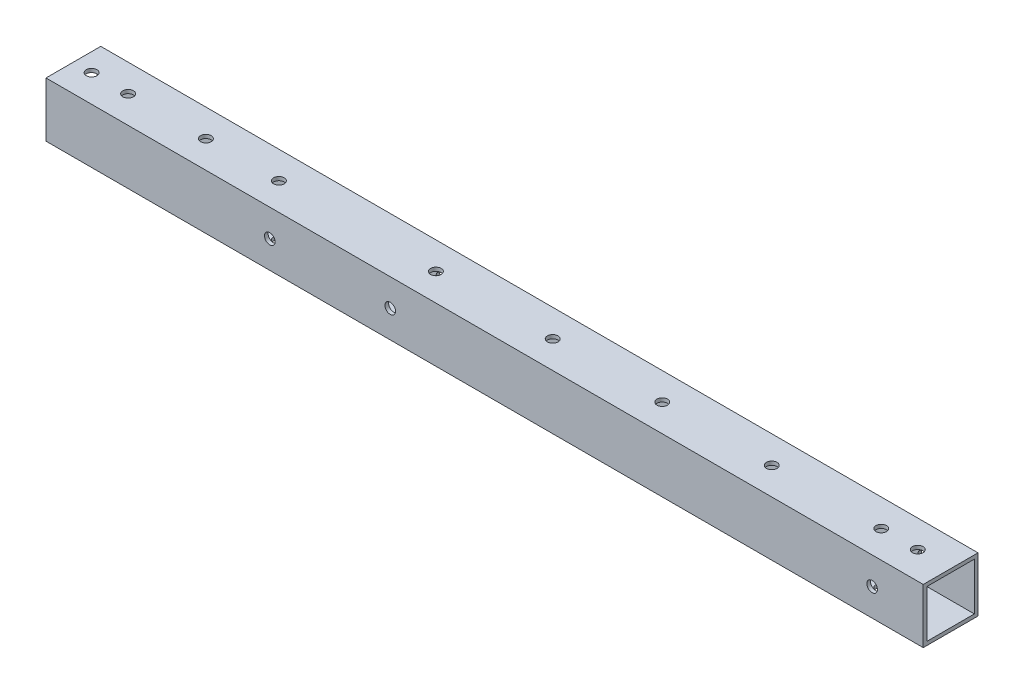
SolidWorks part; units mm, degrees
material "Thornel Mat VMA"
ref_plane "前视基准面" through (0, 0, 0) normal (0, 0, 1) x (1, 0, 0)
ref_plane "上视基准面" through (0, 0, 0) normal (0, 1, 0) x (1, 0, 0)
ref_plane "右视基准面" through (0, 0, 0) normal (1, 0, 0) x (0, 0, -1)
other "Configuration Table"
sketch "草图1" plane through (0, 0, 0) normal (1, 0, 0) x (0, 0, -1)
  line L0 (-6.5, -6.5) -> (-6.5, 6.5)
  line L1 (-7.5, -7.5) -> (7.5, -7.5)
  line L2 (-7.5, -7.5) -> (-7.5, 7.5)
  line L3 (-7.5, 7.5) -> (7.5, 7.5)
  line L4 (7.5, -7.5) -> (7.5, 7.5)
  line L5 (-7.5, -7.5) -> (7.5, 7.5) construction
  line L6 (-7.5, 7.5) -> (7.5, -7.5) construction
  line L7 (-6.5, 6.5) -> (6.5, 6.5)
  line L8 (6.5, -6.5) -> (6.5, 6.5)
  line L9 (-6.5, -6.5) -> (6.5, -6.5)
  point P0 (0, 0)
  dimension "D1" = 15
  dimension "D2" = 15
  dimension "D3" = 1
extrude "凸台-拉伸1" add sketch "草图1" along normal blind 240.3
sketch "草图2" plane through (0, 7.5, 0) normal (0, 1, 0) x (1, 0, 0)
  line L0 (0, 0) -> (271.1797, 0) construction
  circle A0 centre (5, 0) radius 1.45 construction
  circle A1 centre (15, 0) radius 1.45 construction
  circle A2 centre (36.3015, 0) radius 1.45 construction
  circle A3 centre (56.3015, 0) radius 1.45 construction
  circle A4 centre (99.3015, 0) radius 1.45 construction
  circle A5 centre (221.3015, 0) radius 1.45 construction
  circle A6 centre (231.3015, 0) radius 1.45 construction
  circle A7 centre (5, 0) radius 1.45
  circle A8 centre (15, 0) radius 1.45
  circle A9 centre (36.3015, 0) radius 1.45
  circle A10 centre (56.3015, 0) radius 1.45
  circle A11 centre (99.3015, 0) radius 1.45
  circle A12 centre (221.3015, 0) radius 1.45
  circle A13 centre (231.3015, 0) radius 1.45
  circle A14 centre (131.3015, 0) radius 1.45
  circle A15 centre (161.3015, 0) radius 1.45
  circle A16 centre (191.3015, 0) radius 1.45
  point P30 (161.3015, 0)
  dimension "D1" = 32
  dimension "D2" = 2.9
  dimension "D3" = 30
  dimension "D4" = 30
extrude "切除-拉伸1" cut sketch "草图2" against normal through all
sketch "草图3" plane through (0, 0, 7.5) normal (0, 0, 1) x (1, 0, 0)
  circle A0 centre (61.3015, 0) radius 1.45 construction
  circle A1 centre (61.3015, 0) radius 1.45
  circle A2 centre (226.3015, 0) radius 1.45 construction
  circle A3 centre (94.3015, 0) radius 1.45 construction
  circle A4 centre (226.3015, 0) radius 1.45
  circle A5 centre (94.3015, 0) radius 1.45
extrude "切除-拉伸2" cut sketch "草图3" against normal through all
